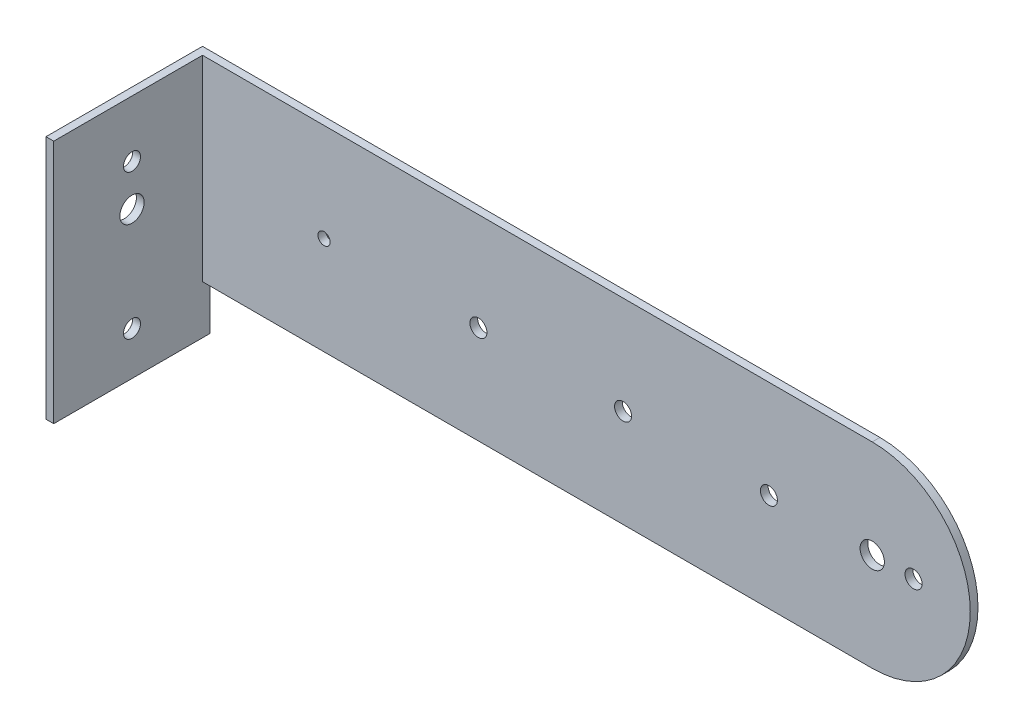
SolidWorks part; units mm, degrees
ref_plane "Front Plane" through (0, 0, 0) normal (0, 0, 1) x (1, 0, 0)
ref_plane "Top Plane" through (0, 0, 0) normal (0, 1, 0) x (1, 0, 0)
ref_plane "Right Plane" through (0, 0, 0) normal (1, 0, 0) x (0, 0, -1)
sketch "Sketch1" plane through (0, 0, 0) normal (0, 0, 1) x (1, 0, 0)
  line L0 (-39.61, 20.1682) -> (39.61, 20.1682)
  line L1 (-39.61, -20.1682) -> (39.61, -20.1682)
  line L2 (-39.61, 20.1682) -> (-99.73, 20.1682)
  line L3 (-99.73, 20.1682) -> (-99.73, -20.1682)
  line L4 (-99.73, -20.1682) -> (-39.61, -20.1682)
  arc A1 (39.61, -20.1682) -> (39.61, 20.1682) centre (39.61, 0) ccw
  point P8 (0, 20.1682)
  point P9 (0, -20.1682)
  dimension "D1" = 99.73
  dimension "D2" = 139.34
  dimension "D3" = 40.3364
extrude "Boss-Extrude1" add sketch "Sketch1" along normal blind 1.59
sketch "Sketch2" plane through (0, 0, 1.59) normal (0, 0, 1) x (1, 0, 0)
  circle A0 centre (39.61, 0) radius 2.5
  arc A1 (39.61, -20.1682) -> (39.61, 20.1682) centre (39.61, 0) ccw construction
  circle A2 centre (48.11, 0) radius 1.75
  circle A3 centre (18.36, 0) radius 1.75
  circle A4 centre (-11.64, 0) radius 1.75
  circle A5 centre (-41.39, 0) radius 1.75
  dimension "D1" = 5
  dimension "D4" = 3.5
  dimension "D9" = 3.5
  dimension "D10" = 3.5
  dimension "D2" = 8.5
  dimension "D3" = 29.75
  dimension "D5" = 29.75
  dimension "D6" = 30
extrude "Cut-Extrude2" cut sketch "Sketch2" against normal blind 1.59
sketch "Sketch3" plane through (0, 0, 1.59) normal (0, 0, 1) x (1, 0, 0)
  line L0 (39.61, 20.1682) -> (-99.73, 20.1682) construction
  line L1 (-98.14, 20.1682) -> (-99.73, 20.1682)
  line L2 (-98.14, 20.1682) -> (-98.14, -20.1682)
  line L3 (-98.14, -20.1682) -> (-99.73, -20.1682)
  line L4 (-99.73, 20.1682) -> (-99.73, -20.1682)
  dimension "D1" = 1.59
extrude "Boss-Extrude2" add sketch "Sketch3" along normal blind 30.602
sketch "Sketch4" [suppressed] plane through (-99.73, 0, 0) normal (-1, 0, 0) x (0, 0, 1)
  line L0 (0, 0) -> (41.59, 0) construction
  line L1 (41.59, 20.1682) -> (41.59, -20.1682) construction
  line L2 (20.795, 20.1682) -> (20.795, -20.1682) construction
  line L3 (41.59, 20.1682) -> (0, 20.1682) construction
  line L4 (41.59, -20.1682) -> (0, -20.1682) construction
  circle A0 centre (20.795, 0) radius 7.5 construction
  circle A1 centre (20.795, 7.5) radius 0.75
  circle A2 centre (13.295, 0) radius 0.75
  circle A3 centre (28.295, 0) radius 0.75
  circle A4 centre (20.795, -7.5) radius 0.75
  dimension "D1" = 15
  dimension "D2" = 1.5
  dimension "D3" = 1.5
extrude "Cut-Extrude3" [suppressed] cut sketch "Sketch4" against normal blind 40
sketch "Sketch5" plane through (-99.73, 0, 0) normal (-1, 0, 0) x (0, 0, 1)
  line L0 (16.096, 20.1682) -> (16.096, -20.1682) construction
  line L1 (32.192, 20.1682) -> (0, 20.1682) construction
  line L2 (32.192, -20.1682) -> (0, -20.1682) construction
  circle A0 centre (16.096, 0) radius 2.5
  circle A1 centre (16.096, 8.5) radius 1.75
  circle A2 centre (16.096, -21.25) radius 1.75
  dimension "D1" = 5
  dimension "D4" = 3.5
  dimension "D5" = 3.5
  dimension "D2" = 8.5
  dimension "D3" = 29.75
extrude "Cut-Extrude4" cut sketch "Sketch5" against normal blind 10
sketch "Sketch6" plane through (-99.73, 0, 0) normal (-1, 0, 0) x (0, 0, 1)
  line L1 (0, -20.1682) -> (32.192, -20.1682)
  line L2 (0, -20.1682) -> (0, -30.1682)
  line L3 (0, -30.1682) -> (32.192, -30.1682)
  line L4 (32.192, -20.1682) -> (32.192, -30.1682)
  dimension "D1" = 10
extrude "Boss-Extrude3" add sketch "Sketch6" against normal up to surface (1.59 mm away) up to face at (-98.14, 6.75, 16.096)
sketch "Sketch7" plane through (-99.73, 0, 0) normal (-1, 0, 0) x (0, 0, 1)
  circle A0 centre (16.096, -21.25) radius 1.75
  dimension "D1" = 3.5
extrude "Cut-Extrude5" cut sketch "Sketch7" against normal blind 10
sketch "Sketch8" plane through (0, 0, 1.59) normal (0, 0, 1) x (1, 0, 0)
  line L0 (-98.14, -30.1682) -> (-98.14, 20.1682) construction
  circle A0 centre (-73.14, 0) radius 1.25
  dimension "D2" = 2.5
  dimension "D1" = 25
extrude "Cut-Extrude6" cut sketch "Sketch8" against normal blind 10
